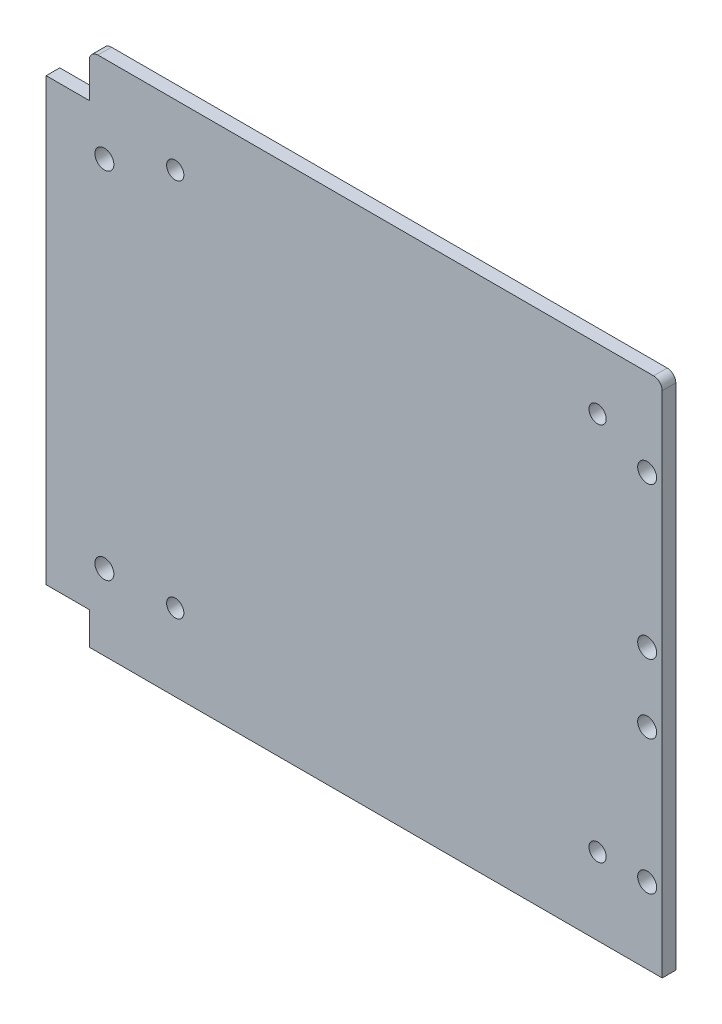
SolidWorks part; units mm, degrees
ref_plane "Front Plane" through (0, 0, 0) normal (0, 0, 1) x (1, 0, 0)
ref_plane "Top Plane" through (0, 0, 0) normal (0, 1, 0) x (1, 0, 0)
ref_plane "Right Plane" through (0, 0, 0) normal (1, 0, 0) x (0, 0, -1)
sketch "BPR2 PCB Outline" plane through (0, 0, 0) normal (0, 0, 1) x (1, 0, 0)
  line L1 (56.571, 67.3176) -> (121.041, 67.3176)
  line L2 (55.571, 66.3176) -> (55.571, 6.8176)
  line L3 (55.571, 6.8176) -> (83.597, 6.8176)
  line L4 (122.041, 66.3176) -> (122.041, 7.8176)
  line L5 (83.597, 6.8176) -> (103.597, 6.8176)
  line L7 (103.597, 6.8176) -> (121.041, 6.8176)
  arc A0 (121.041, 6.8176) -> (122.041, 7.8176) centre (121.041, 7.8176) ccw
  arc A1 (121.041, 67.3176) -> (122.041, 66.3176) centre (121.041, 66.3176) cw
  arc A2 (56.571, 67.3176) -> (55.571, 66.3176) centre (56.571, 66.3176) ccw
  point P6 (122.041, 6.8176)
  point P9 (122.041, 67.3176)
  point P12 (55.571, 67.3176)
  dimension "D2" = 66.47
  dimension "D3" = 1
  dimension "D1" = 60.5
extrude "Boss-Extrude1" add sketch "BPR2 PCB Outline" against normal blind 1.5748
ref_plane "Plane1" through (55.571, 6.8176, 0) normal (0, 0, 1) x (1, 0, 0)
sketch "Sketch8" plane through (55.571, 6.8176, 0) normal (0, 0, 1) x (1, 0, 0)
  line L1 (0, 0) -> (66.47, 0)
  line L2 (0, 0) -> (0, 1)
  line L3 (0, 1) -> (66.47, 1)
  line L4 (66.47, 0) -> (66.47, 1)
sketch "Sketch9" plane through (0, 0, 0) normal (0, 0, 1) x (1, 0, 0)
  line L0 (122.041, 7.8176) -> (122.041, 66.3176) construction
  line L1 (55.571, 6.8176) -> (122.041, 6.8176)
  line L2 (55.571, 6.8176) -> (55.571, 8.3176)
  line L3 (55.571, 8.3176) -> (122.041, 8.3176)
  line L4 (122.041, 6.8176) -> (122.041, 8.3176)
  dimension "D1" = 1.5
sketch "Sketch10" plane through (0, 0, 0) normal (0, 0, 1) x (1, 0, 0)
  line L0 (122.041, 7.8176) -> (122.041, 66.3176) construction
  line L1 (55.571, 6.8176) -> (122.041, 6.8176)
  line L2 (55.571, 6.8176) -> (55.571, 10.9923)
  line L3 (55.571, 10.9923) -> (122.041, 10.9923)
  line L4 (122.041, 6.8176) -> (122.041, 10.9923)
extrude "Boss-Extrude3" add sketch "Sketch10" against normal blind 1.575
sketch "Sketch11" plane through (0, 0, 0) normal (0, 0, 1) x (1, 0, 0)
  line L0 (122.041, 6.8176) -> (122.041, 66.3176) construction
  line L1 (55.571, 6.8176) -> (122.041, 6.8176)
  line L2 (55.571, 6.8176) -> (55.571, 7.3176)
  line L3 (55.571, 7.3176) -> (122.041, 7.3176)
  line L4 (122.041, 6.8176) -> (122.041, 7.3176)
  dimension "D1" = 0.5
extrude "Cut-Extrude2" cut sketch "Sketch11" against normal through all
hole_wizard "M2 Clearance Hole1" positions "Sketch3" profile "Sketch4" hole size "M2" standard "ISO" end condition through all
sketch "Sketch3" plane through (39.2609, 104.2046, -6.5748) normal (0, 0, -1) x (1, 0, 0)
  point P0 (81.0301, 88.112)
  point P4 (81.0301, 72.537)
  point P7 (81.0301, 64.537)
  point P10 (81.0301, 46.962)
  point P13 (18.0601, 46.962)
  point P16 (18.0601, 88.112)
  point P19 (18.0601, 88.112)
sketch "Sketch4" plane through (120.291, 16.0926, -6.5748) normal (1, 0, 0) x (0, 1, 0)
  line L0 (0, 0) -> (0, 6.5748)
  line L1 (0, 6.5748) -> (1.1, 6.5748)
  line L2 (1.1, 6.5748) -> (1.1, 0)
  line L3 (1.1, 0) -> (0, 0)
  line L4 (0, -6.35) -> (0, 107.95) construction
  dimension "Thru Hole Dia." = 2.2
  dimension "Thru Hole Depth" = 6.5748
hole_wizard "Ø2.0mm Dowel Hole1" positions "Sketch5" profile "Sketch6" hole size "Ø3.0" standard "ANSI Metric" end condition through all
sketch "Sketch5" plane through (39.2609, 104.2046, -4.6498) normal (0, 0, -1) x (1, 0, 0)
  point P0 (26.2801, 87.962)
  point P3 (26.2801, 43.962)
  point P6 (75.2801, 43.962)
  point P9 (75.2801, 87.962)
sketch "Sketch6" plane through (65.541, 16.2426, -4.6498) normal (1, 0, 0) x (0, 1, 0)
  line L0 (0, 0) -> (0, 4.6498)
  line L1 (0, 4.6498) -> (1, 4.6498)
  line L2 (1, 4.6498) -> (1, 0)
  line L3 (1, 0) -> (0, 0)
  line L4 (0, -6.35) -> (0, 107.95) construction
  dimension "Thru Hole Dia." = 2
  dimension "Thru Hole Depth" = 4.6498
sketch "Sketch12" plane through (0, 0, 0) normal (0, 0, 1) x (1, 0, 0)
  line L0 (-951.145, 11.0926) -> (49048.855, 11.0926) construction
  line L1 (-951.145, 62.2426) -> (49048.855, 62.2426) construction
  line L2 (55.571, 66.3176) -> (55.571, 7.3176) construction
  line L4 (50.571, -954.0038) -> (50.571, 49045.9962) construction
  line L5 (55.571, -946.3095) -> (55.571, 49053.6905) construction
  line L7 (50.571, 11.0926) -> (55.571, 11.0926)
  line L8 (50.571, 11.0926) -> (50.571, 62.2426)
  line L9 (50.571, 62.2426) -> (55.571, 62.2426)
  line L10 (55.571, 11.0926) -> (55.571, 62.2426)
  dimension "D1" = 5
  dimension "D2" = 5
  dimension "D3" = 5
extrude "Boss-Extrude4" add sketch "Sketch12" against normal through all contours L8 L9 L10 L7
